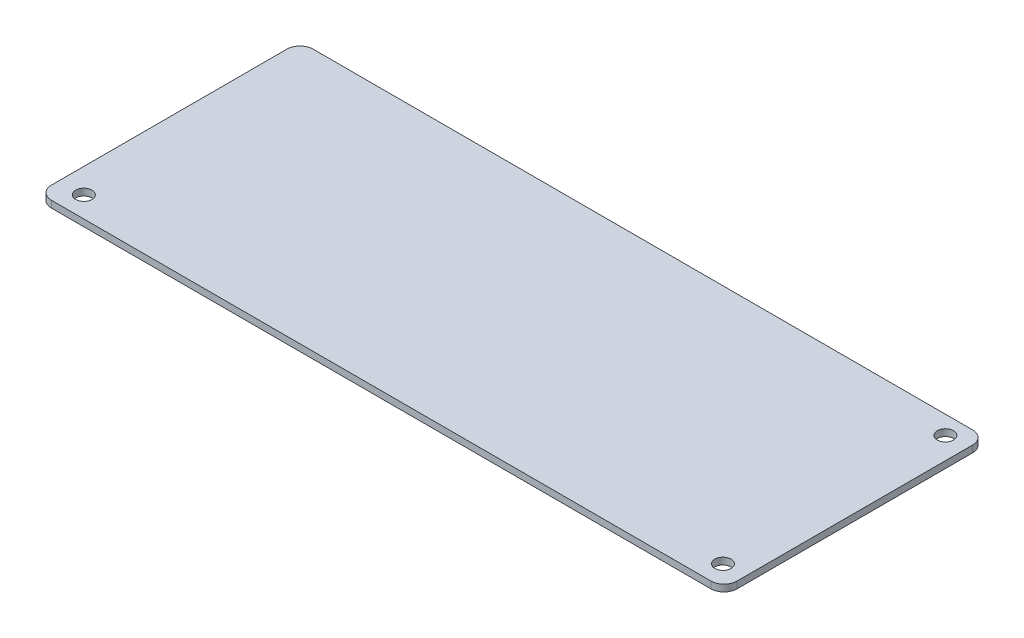
SolidWorks part; units mm, degrees
ref_plane "Front Plane" through (0, 0, 0) normal (0, 0, 1) x (1, 0, 0)
ref_plane "Top Plane" through (0, 0, 0) normal (0, 1, 0) x (1, 0, 0)
ref_plane "Right Plane" through (0, 0, 0) normal (1, 0, 0) x (0, 0, -1)
sketch "Sketch1" plane through (0, 0, 0) normal (0, 1, 0) x (1, 0, 0)
  line L1 (63, -25) -> (-63, -25)
  line L2 (65.5, -22.5) -> (65.5, 22.5)
  line L3 (63, 25) -> (-63, 25)
  line L4 (-65.5, -22.5) -> (-65.5, 22.5)
  line L5 (65.5, -25) -> (-65.5, 25) construction
  line L6 (65.5, 25) -> (-65.5, -25) construction
  arc A0 (-63, 25) -> (-65.5, 22.5) centre (-63, 22.5) ccw
  arc A1 (-63, -25) -> (-65.5, -22.5) centre (-63, -22.5) cw
  arc A2 (63, -25) -> (65.5, -22.5) centre (63, -22.5) ccw
  arc A3 (65.5, 22.5) -> (63, 25) centre (63, 22.5) ccw
  point P0 (0, 0)
  dimension "D3" = 2.5
  dimension "D1" = 131
  dimension "D2" = 50
extrude "Boss-Extrude1" add sketch "Sketch1" along normal blind 1.3
sketch "Sketch2" plane through (0, 1.3, 0) normal (0, 1, 0) x (1, 0, 0)
  line L0 (-65.5, -22.5) -> (-65.5, -25) construction
  line L1 (-65.5, 22.5) -> (-65.5, -22.5) construction
  line L2 (-65.5, -25) -> (-60.8, -25) construction
  line L3 (-63, -25) -> (63, -25) construction
  line L4 (-60.8, -25) -> (-60.8, -21) construction
  line L5 (-60.8, -21) -> (61.3, -21) construction
  line L6 (61.3, -21) -> (61.3, 21.5) construction
  arc A0 (-65.5, -22.5) -> (-63, -25) centre (-63, -22.5) ccw construction
  circle A1 centre (-60.8, -21) radius 1.55
  circle A2 centre (61.3, 21.5) radius 1.55
  circle A3 centre (61.3, -21) radius 1.55
  dimension "D1" = 4
  dimension "D2" = 4.7
  dimension "D3" = 122.1
  dimension "D4" = 42.5
extrude "Cut-Extrude1" cut sketch "Sketch2" against normal blind 5.3
